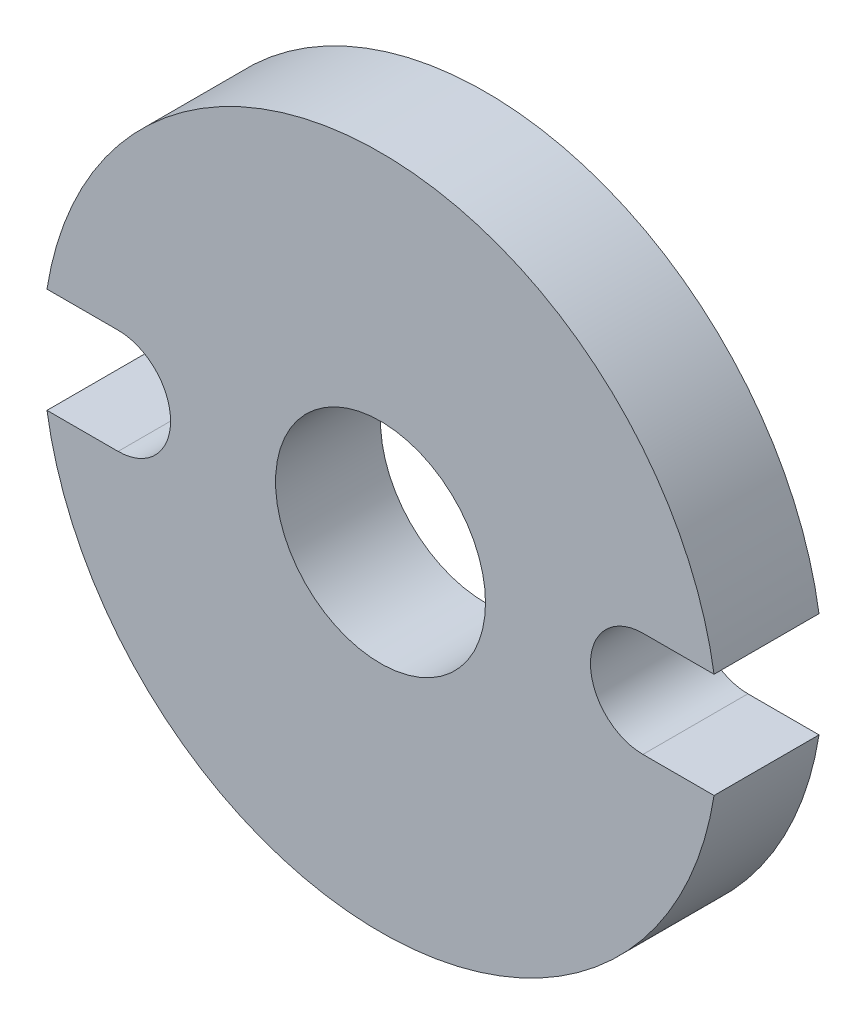
SolidWorks part; units mm, degrees
material "ABS"
ref_plane "Спереди" through (0, 0, 0) normal (0, 0, 1) x (1, 0, 0)
ref_plane "Сверху" through (0, 0, 0) normal (0, 1, 0) x (1, 0, 0)
ref_plane "Справа" through (0, 0, 0) normal (1, 0, 0) x (0, 0, -1)
sketch "Эскиз1" plane through (0, 0, 0) normal (0, 0, 1) x (1, 0, 0)
  line L0 (-8.75, 0) -> (-3.75, 0) construction
  line L1 (-8.75, 0.75) -> (-3.75, 0.75)
  line L2 (-8.75, -0.75) -> (-3.75, -0.75)
  line L3 (0, 0) -> (0, 4.1546) construction
  line L4 (8.75, 0) -> (3.75, 0) construction
  line L5 (8.75, 0.75) -> (3.75, 0.75)
  line L6 (8.75, -0.75) -> (3.75, -0.75)
  circle A0 centre (0, 0) radius 4.825
  circle A1 centre (0, 0) radius 1.5
  arc A2 (-8.75, 0.75) -> (-8.75, -0.75) centre (-8.75, 0) ccw
  arc A3 (-3.75, -0.75) -> (-3.75, 0.75) centre (-3.75, 0) ccw
  arc A4 (8.75, 0.75) -> (8.75, -0.75) centre (8.75, 0) cw
  arc A5 (3.75, -0.75) -> (3.75, 0.75) centre (3.75, 0) cw
  circle A6 centre (0, 0) radius 3 construction
  point P6 (-6.25, 0)
  point P14 (6.25, 0)
  dimension "D1" = 9.65
  dimension "D2" = 3
  dimension "D5" = 6
  dimension "D3" = 1.5
  dimension "D4" = 5
extrude "Бобышка-Вытянуть1" add sketch "Эскиз1" along normal blind 1.5 contours L6 A5 L5 A0 L1 A3 L2 A1
